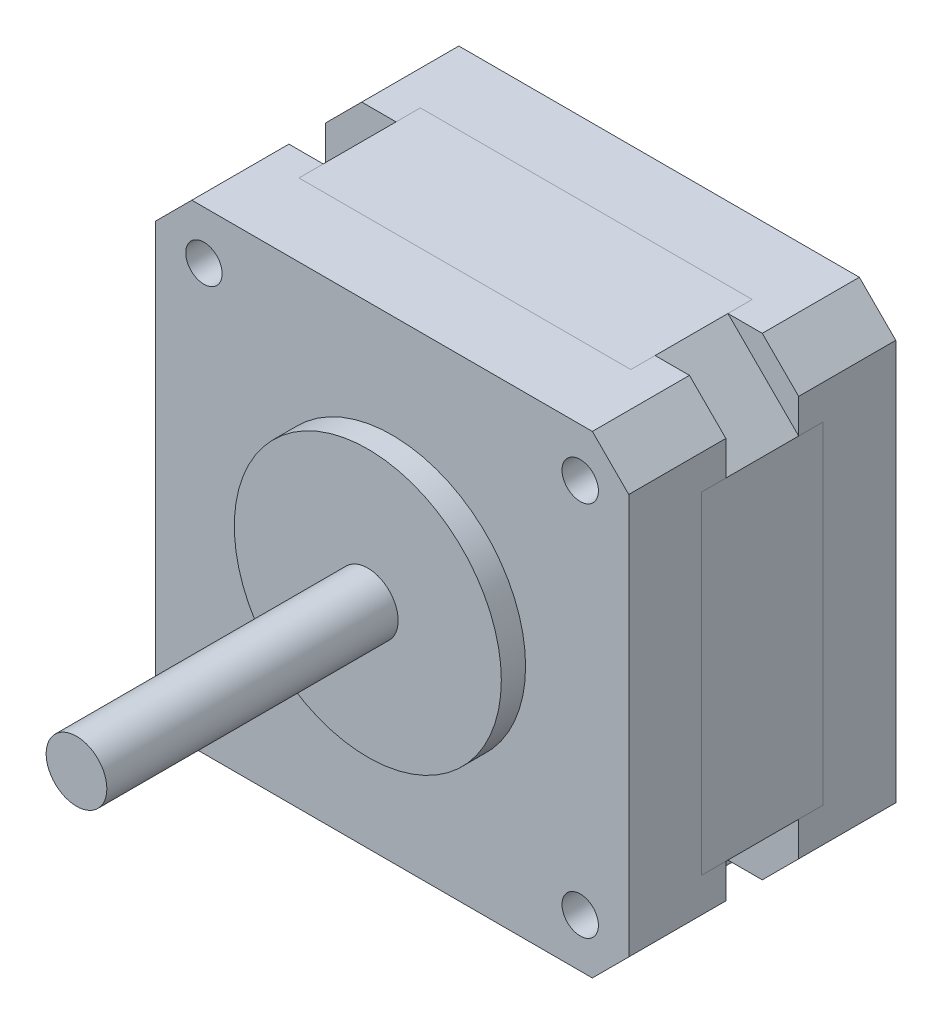
SolidWorks part; units mm, degrees
ref_plane "Front Plane" through (0, 0, 0) normal (0, 0, 1) x (1, 0, 0)
ref_plane "Top Plane" through (0, 0, 0) normal (0, 1, 0) x (1, 0, 0)
ref_plane "Right Plane" through (0, 0, 0) normal (1, 0, 0) x (0, 0, -1)
sketch "Sketch1" plane through (0, 0, 0) normal (0, 0, 1) x (1, 0, 0)
  line L0 (-19.5, 16.5) -> (-16.5, 19.5)
  line L1 (-16.5, 19.5) -> (16.5, 19.5)
  line L2 (-19.5, 16.5) -> (-19.5, -16.5)
  line L3 (-16.5, -19.5) -> (16.5, -19.5)
  line L4 (19.5, 16.5) -> (19.5, -16.5)
  line L5 (-19.5, 19.5) -> (19.5, -19.5) construction
  line L6 (-19.5, -19.5) -> (19.5, 19.5) construction
  line L7 (16.5, 19.5) -> (19.5, 16.5)
  line L8 (16.5, -19.5) -> (19.5, -16.5)
  line L9 (-19.5, -16.5) -> (-16.5, -19.5)
  point P0 (0, 0)
  dimension "D1" = 39
  dimension "D2" = 39
extrude "Boss-Extrude1" add sketch "Sketch1" along normal blind 8
sketch "Sketch2" plane through (0, 0, 8) normal (0, 0, 1) x (1, 0, 0)
  line L0 (-19.5, 13.6716) -> (-13.6716, 19.5)
  line L3 (-16.5, 19.5) -> (-19.5, 16.5) construction
  line L4 (13.6716, 19.5) -> (19.5, 13.6716)
  line L5 (19.5, -13.6716) -> (13.6716, -19.5)
  line L6 (-13.6716, -19.5) -> (-19.5, -13.6716)
  line L7 (-19.5, 13.6716) -> (-19.5, -13.6716)
  line L8 (-13.6716, 19.5) -> (13.6716, 19.5)
  line L9 (19.5, 13.6716) -> (19.5, -13.6716)
  line L10 (13.6716, -19.5) -> (-13.6716, -19.5)
  line L12 (16.5, 19.5) -> (-16.5, 19.5) construction
  point P2 (0, 0)
  point P4 (0, 0)
  point P8 (0, 0)
  point P9 (1.8832, -1.8832)
  point P10 (0, 0)
  point P17 (0, 0)
  dimension "D1" = 2
  dimension "D2" = 4
extrude "Cut-Extrude1" cut sketch "Sketch2" against normal blind 2
ref_plane "Plane2" through (0, 0, 22) normal (0, 0, -1) x (-1, 0, 0)
sketch "Sketch8" plane through (0, 0, 22) normal (0, 0, -1) x (-1, 0, 0)
  line L8 (19.5, 16.5) -> (16.5, 19.5)
  line L9 (16.5, 19.5) -> (-16.5, 19.5)
  line L10 (-16.5, 19.5) -> (-19.5, 16.5)
  line L11 (-19.5, 16.5) -> (-19.5, -16.5)
  line L12 (-19.5, -16.5) -> (-16.5, -19.5)
  line L13 (-16.5, -19.5) -> (16.5, -19.5)
  line L14 (16.5, -19.5) -> (19.5, -16.5)
  line L15 (19.5, -16.5) -> (19.5, 16.5)
  line L16 (19.5, 16.5) -> (16.5, 19.5)
  line L17 (16.5, 19.5) -> (-16.5, 19.5)
  line L18 (-16.5, 19.5) -> (-19.5, 16.5)
  line L19 (-19.5, 16.5) -> (-19.5, -16.5)
  line L20 (-19.5, -16.5) -> (-16.5, -19.5)
  line L21 (-16.5, -19.5) -> (16.5, -19.5)
  line L22 (16.5, -19.5) -> (19.5, -16.5)
  line L23 (19.5, -16.5) -> (19.5, 16.5)
  dimension "D1" = 0
extrude "Boss-Extrude7" add sketch "Sketch8" along normal blind 8 separate body
sketch "草图4" plane through (0, 0, 6) normal (0, 0, 1) x (1, 0, 0)
  line L8 (-13.6716, 19.5) -> (-19.5, 13.6716)
  line L9 (-19.5, 13.6716) -> (-19.5, -13.6716)
  line L10 (-19.5, -13.6716) -> (-13.6716, -19.5)
  line L11 (-13.6716, -19.5) -> (13.6716, -19.5)
  line L12 (13.6716, -19.5) -> (19.5, -13.6716)
  line L13 (19.5, -13.6716) -> (19.5, 13.6716)
  line L14 (19.5, 13.6716) -> (13.6716, 19.5)
  line L15 (13.6716, 19.5) -> (-13.6716, 19.5)
  line L16 (-13.6716, 19.5) -> (-19.5, 13.6716)
  line L17 (-19.5, 13.6716) -> (-19.5, -13.6716)
  line L18 (-19.5, -13.6716) -> (-13.6716, -19.5)
  line L19 (-13.6716, -19.5) -> (13.6716, -19.5)
  line L20 (13.6716, -19.5) -> (19.5, -13.6716)
  line L21 (19.5, -13.6716) -> (19.5, 13.6716)
  line L22 (19.5, 13.6716) -> (13.6716, 19.5)
  line L23 (13.6716, 19.5) -> (-13.6716, 19.5)
  dimension "D1" = 0
extrude "凸台-拉伸3" add sketch "草图4" along normal blind 10 separate body
sketch "Sketch9" plane through (0, 0, 14) normal (0, 0, -1) x (-1, 0, 0)
  line L8 (13.6716, -19.5) -> (19.5, -13.6716)
  line L9 (-13.6716, -19.5) -> (13.6716, -19.5)
  line L10 (-19.5, -13.6716) -> (-13.6716, -19.5)
  line L11 (-19.5, 13.6716) -> (-19.5, -13.6716)
  line L12 (-13.6716, 19.5) -> (-19.5, 13.6716)
  line L13 (13.6716, 19.5) -> (-13.6716, 19.5)
  line L14 (19.5, 13.6716) -> (13.6716, 19.5)
  line L15 (19.5, -13.6716) -> (19.5, 13.6716)
  line L16 (13.6716, -19.5) -> (19.5, -13.6716)
  line L17 (-13.6716, -19.5) -> (13.6716, -19.5)
  line L18 (-19.5, -13.6716) -> (-13.6716, -19.5)
  line L19 (-19.5, 13.6716) -> (-19.5, -13.6716)
  line L20 (-13.6716, 19.5) -> (-19.5, 13.6716)
  line L21 (13.6716, 19.5) -> (-13.6716, 19.5)
  line L22 (19.5, 13.6716) -> (13.6716, 19.5)
  line L23 (19.5, -13.6716) -> (19.5, 13.6716)
  dimension "D1" = 0
extrude "Cut-Extrude2" cut sketch "Sketch9" against normal blind 2
sketch "Sketch10" plane through (0, 0, 22) normal (0, 0, 1) x (1, 0, 0)
  circle A0 centre (-15.5, 15.5) radius 1.5
  circle A1 centre (15.5, 15.5) radius 1.5
  circle A2 centre (15.5, -15.5) radius 1.5
  circle A3 centre (-15.5, -15.5) radius 1.5
  dimension "D5" = 3
  dimension "D1" = 31
  dimension "D2" = 15.5
  dimension "D3" = 31
  dimension "D4" = 15.5
extrude "Cut-Extrude3" cut sketch "Sketch10" against normal blind 5.5
sketch "Sketch11" plane through (0, 0, 22) normal (0, 0, 1) x (1, 0, 0)
  circle A0 centre (0, 0) radius 11
  dimension "D1" = 22
extrude "Boss-Extrude9" add sketch "Sketch11" along normal blind 2 separate body
sketch "Sketch12" plane through (0, 0, 24) normal (0, 0, 1) x (1, 0, 0)
  circle A0 centre (0, 0) radius 2.5
  dimension "D1" = 5
extrude "Boss-Extrude10" add sketch "Sketch12" along normal blind 24 separate body
sketch "Sketch14" plane through (0, 0, 0) normal (0, 0, -1) x (-1, 0, 0)
  circle A1 centre (15.5, -15.5) radius 1.5
  circle A2 centre (15.5, -15.5) radius 1.5
  circle A3 centre (-15.5, -15.5) radius 1.5
  circle A4 centre (-15.5, -15.5) radius 1.5
  circle A5 centre (-15.5, 15.5) radius 1.5
  circle A6 centre (-15.5, 15.5) radius 1.5
  circle A7 centre (15.5, 15.5) radius 1.5
  circle A8 centre (15.5, 15.5) radius 1.5
  dimension "D1" = 0
  dimension "D2" = 0
  dimension "D3" = 0
  dimension "D4" = 0
extrude "Cut-Extrude5" cut sketch "Sketch14" against normal blind 5.5
sketch "Sketch16" plane through (0, 0, 0) normal (0, 0, -1) x (-1, 0, 0)
  circle A0 centre (0, 0) radius 2.5 construction
  circle A1 centre (0, 0) radius 4
  dimension "D1" = 5
  dimension "D2" = 8
extrude "Cut-Extrude6" cut sketch "Sketch16" against normal blind 2
sketch "Sketch17" plane through (0, 0, 2) normal (0, 0, -1) x (-1, 0, 0)
  circle A0 centre (0, 0) radius 2.5
  dimension "D1" = 5
extrude "Boss-Extrude11" add sketch "Sketch17" along normal blind 1 separate body
sketch "Sketch18" plane through (0, 0, 0) normal (0, 0, -1) x (-1, 0, 0)
  circle A0 centre (15.5, -15.5) radius 2.75
  circle A1 centre (-15.5, -15.5) radius 2.75
  circle A2 centre (-15.5, 15.5) radius 2.75
  circle A3 centre (15.5, 15.5) radius 2.75
  point P12 (0, 0)
  dimension "D1" = 5.5
  dimension "D2" = 4
extrude "Cut-Extrude7" cut sketch "Sketch18" against normal blind 1
ref_plane "基准面1" through (0, -19.5, 0) normal (0, -1, 0) x (-1, 0, 0)
sketch "草图3" plane through (0, -19.5, 0) normal (0, -1, 0) x (-1, 0, 0)
  line L0 (16.5, 0) -> (-16.5, 0) construction
  line L1 (-11, 0) -> (11, 0)
  line L2 (-11, 0) -> (-11, -7.5)
  line L3 (-11, -7.5) -> (11, -7.5)
  line L4 (11, 0) -> (11, -7.5)
  point P6 (0, -7.5)
  dimension "D1" = 22
  dimension "D2" = 7.5
extrude "凸台-拉伸4" add sketch "草图3" along normal blind 3 separate body
